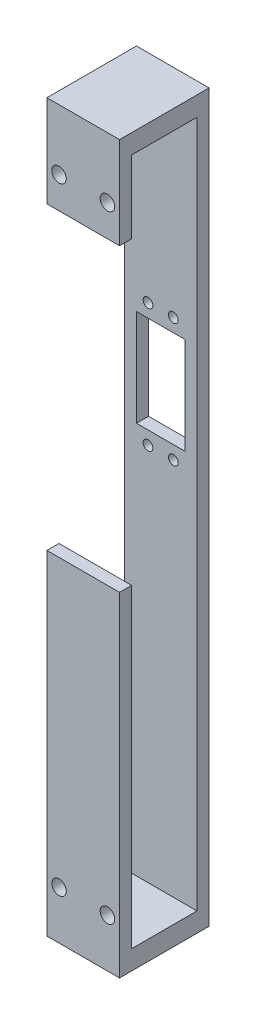
SolidWorks part; units mm, degrees
ref_plane "Front" through (0, 0, 0) normal (0, 0, 1) x (1, 0, 0)
ref_plane "Top" through (0, 0, 0) normal (0, 1, 0) x (1, 0, 0)
ref_plane "Right" through (0, 0, 0) normal (1, 0, 0) x (0, 0, -1)
sketch "草图2" plane through (0, 0, 0) normal (0, 0, 1) x (1, 0, 0)
  line L0 (10, 0) -> (10, 10) construction
  line L1 (0, 0) -> (20, 0)
  line L2 (0, 0) -> (0, -40)
  line L3 (0, -40) -> (20, -40)
  line L4 (20, 0) -> (20, -40)
  line L6 (10, 10) -> (25, 10) construction
  line L7 (10, -50) -> (25, -50) construction
  line L8 (25, -50) -> (-5, -50)
  line L9 (25, 10) -> (25, -50)
  line L10 (-5, -50) -> (-5, 10)
  line L11 (-5, 10) -> (25, 10)
  dimension "D1" = 20
  dimension "D2" = 40
extrude "凸台-拉伸1" add sketch "草图2" along normal blind 5
sketch "草图3" plane through (0, 0, 5) normal (0, 0, 1) x (1, 0, 0)
  line L4 (15.25, 3.5) -> (15.25, 5.5)
  line L5 (15.25, -43.5) -> (15.25, -45.5)
  line L6 (4.75, 3.5) -> (4.75, 5.5)
  line L7 (4.75, -43.5) -> (4.75, -45.5)
  circle A0 centre (15.25, 5.5) radius 2
  circle A1 centre (15.25, -45.5) radius 2
  circle A2 centre (4.75, -45.5) radius 2
  circle A3 centre (4.75, 5.5) radius 2
extrude "切除-拉伸1" cut sketch "草图3" against normal blind 5
sketch "草图5" plane through (25, 0, 0) normal (1, 0, 0) x (0, 0, -1)
  line L0 (-5, -42) -> (-5, -40)
  line L1 (-5, -50) -> (-5, 10) construction
  line L3 (-5, -50) -> (0, -50)
  line L4 (-5, -50) -> (0, -50) construction
  line L5 (0, -42) -> (0, -40)
  line L8 (-5, -40) -> (0, -40)
  line L9 (0, -50) -> (20, -50)
  line L10 (3, -45) -> (20, -45)
  line L11 (20, -45) -> (20, -50)
  line L13 (-5, -50) -> (-25, -50)
  line L14 (-25, -45) -> (-25, -50)
  line L15 (-8, -45) -> (-25, -45)
  arc A2 (3, -45) -> (0, -42) centre (3, -42) cw
  arc A3 (-5, -42) -> (-8, -45) centre (-8, -42) cw
  point P13 (-5, -40)
  dimension "D1" = 3
ref_plane "基准面1" through (10, 0, 0) normal (1, 0, 0) x (0, 0, -1)
extrude "凸台-拉伸2" add sketch "草图5" along normal blind 5
mirror "镜向1" about plane through (10, 0, 0) normal (1, 0, 0) of "凸台-拉伸2"
sketch "草图6" plane through (0, -45, 0) normal (0, 1, 0) x (1, 0, 0)
  line L0 (30, -2.5) -> (-10, -2.5) construction
  line L1 (30, 0) -> (30, -5) construction
  line L2 (-10, 0) -> (-10, -5) construction
  line L3 (-10, -17.5) -> (-10, 12.5) construction
  line L4 (-10, 20) -> (-10, 3) construction
  line L5 (10, -2.5) -> (10, -23.8536) construction
  line L6 (10, -50) -> (10, 50) construction
  line L7 (30, -17.5) -> (30, 12.5) construction
  line L8 (-10, 12.5) -> (-7.5, 12.5)
  circle A0 centre (-7.5, 12.5) radius 1.5
  circle A1 centre (-7.5, -17.5) radius 1.5
  circle A2 centre (27.5, -17.5) radius 1.5
  circle A3 centre (27.5, 12.5) radius 1.5
extrude "切除-拉伸2" cut sketch "草图6" against normal blind 5
sketch "草图7" plane through (0, 0, 25) normal (0, 0, 1) x (1, 0, 0)
  line L0 (25, -50) -> (25, -40)
  line L1 (25, -40) -> (30, -40)
  line L2 (30, -40) -> (30, -50)
  line L3 (30, -50) -> (25, -50)
  line L4 (-10, -50) -> (-10, -40)
  line L5 (-10, -40) -> (-5, -40) construction
  line L6 (-10, -40) -> (-10, -42) construction
  line L7 (-10, -40) -> (-5, -40)
  line L8 (-5, 10) -> (-5, -40) construction
  line L9 (-5, -40) -> (-5, -50)
  line L10 (-5, -42) -> (-5, -50) construction
  line L11 (-5, -45) -> (-5, -50) construction
  line L12 (-5, -50) -> (-10, -50)
extrude "切除-拉伸3" cut sketch "草图7" against normal blind 100
sketch "草图8" plane through (0, 10, 0) normal (0, 1, 0) x (1, 0, 0)
  line L0 (-5, 0) -> (-5, -5)
  line L1 (-5, -5) -> (25, -5)
  line L2 (25, -5) -> (25, 0)
  line L3 (25, 0) -> (-5, 0)
extrude "凸台-拉伸3" add sketch "草图8" along normal blind 80
sketch "草图9" plane through (0, -50, 0) normal (0, -1, 0) x (1, 0, 0)
  line L0 (25, 0) -> (25, 5)
  line L1 (25, 5) -> (-5, 5)
  line L2 (-5, 5) -> (-5, 0)
  line L3 (-5, 0) -> (25, 0)
extrude "凸台-拉伸4" add sketch "草图9" along normal blind 60
sketch "草图11" plane through (0, 0, 5) normal (0, 0, 1) x (1, 0, 0)
  line L0 (25, -110) -> (25, -102)
  line L1 (25, -110) -> (25, 90) construction
  line L2 (25, -102) -> (-5, -102)
  line L3 (-5, 90) -> (-5, -110) construction
  line L4 (-5, -102) -> (-5, -110)
  line L5 (-5, -110) -> (25, -110)
  line L6 (25, 90) -> (-5, 90)
  line L7 (-5, 90) -> (-5, 82)
  line L8 (-5, 82) -> (25, 82)
  line L9 (25, 82) -> (25, 90)
extrude "凸台-拉伸5" add sketch "草图11" along normal blind 32
sketch "草图13" plane through (0, -102, 0) normal (0, 1, 0) x (1, 0, 0)
  line L0 (25, -37) -> (25, -32)
  line L1 (25, -37) -> (25, 0) construction
  line L2 (25, -32) -> (25, -34.4083)
  line L3 (25, -32) -> (-5, -32)
  line L4 (-5, 0) -> (-5, -37) construction
  line L5 (-5, -32) -> (-5, -37)
  line L6 (-5, -37) -> (25, -37)
  line M6 (-5, -5) -> (-5, -37)
  line M7 (-5, -37) -> (25, -37)
  line M8 (25, -37) -> (25, -5)
extrude "凸台-拉伸6" add sketch "草图13" along normal blind 30 contours L0 L3 M6 M7 M8
sketch "草图14" plane through (0, 82, 0) normal (0, -1, 0) x (1, 0, 0)
  line L0 (-5, 37) -> (-5, 32)
  line L1 (-5, 37) -> (-5, 0) construction
  line L2 (-5, 37) -> (25, 37)
  line L3 (25, 37) -> (25, 32)
  line L4 (25, 32) -> (-5, 32)
extrude "凸台-拉伸7" add sketch "草图14" along normal blind 30
sketch "草图15" plane through (-5, 0, 0) normal (-1, 0, 0) x (0, 0, 1)
  line L4 (37, -110) -> (0, -110)
  line L5 (0, -110) -> (0, -210)
  line L6 (0, -210) -> (37, -210)
  line L7 (37, -210) -> (37, -110)
  dimension "D2" = 100
extrude "凸台-拉伸8" add sketch "草图15" against normal blind 30
sketch "草图12" plane through (0, 0, 5) normal (0, 0, 1) x (1, 0, 0)
  line L0 (10, -102) -> (10, -85) construction
  line L1 (25, -102) -> (-5, -102) construction
  line L3 (10, -102) -> (10, -85) construction
  line L4 (10, 82) -> (10, 65) construction
  line L5 (-5, 82) -> (25, 82) construction
  line L7 (10, 65) -> (0, 65)
  circle A1 centre (0, 65) radius 3
  circle A3 centre (20, 65) radius 3
extrude "切除-拉伸5" cut sketch "草图12" along normal blind 50
sketch "草图16" plane through (25, 0, 0) normal (1, 0, 0) x (0, 0, -1)
  line L0 (-5, -102) -> (-5, -202)
  line L1 (-5, -202) -> (-32, -202)
  line L2 (-5, -202) -> (-5, -210) construction
  line L3 (0, -210) -> (-37, -210) construction
  line L5 (-32, -102) -> (-32, -202)
  line L6 (-5, -102) -> (-32, -102)
  dimension "D1" = 8
  dimension "D2" = 27
extrude "切除-拉伸6" cut sketch "草图16" against normal blind 30
sketch "草图17" plane through (0, 0, 37) normal (0, 0, 1) x (1, 0, 0)
  line L0 (10, -210) -> (10, -190) construction
  line L1 (25, -210) -> (-5, -210) construction
  line L2 (10, -190) -> (20, -190)
  circle A0 centre (20, -190) radius 3
  circle A1 centre (0, -190) radius 3
extrude "切除-拉伸7" cut sketch "草图17" against normal blind 30
